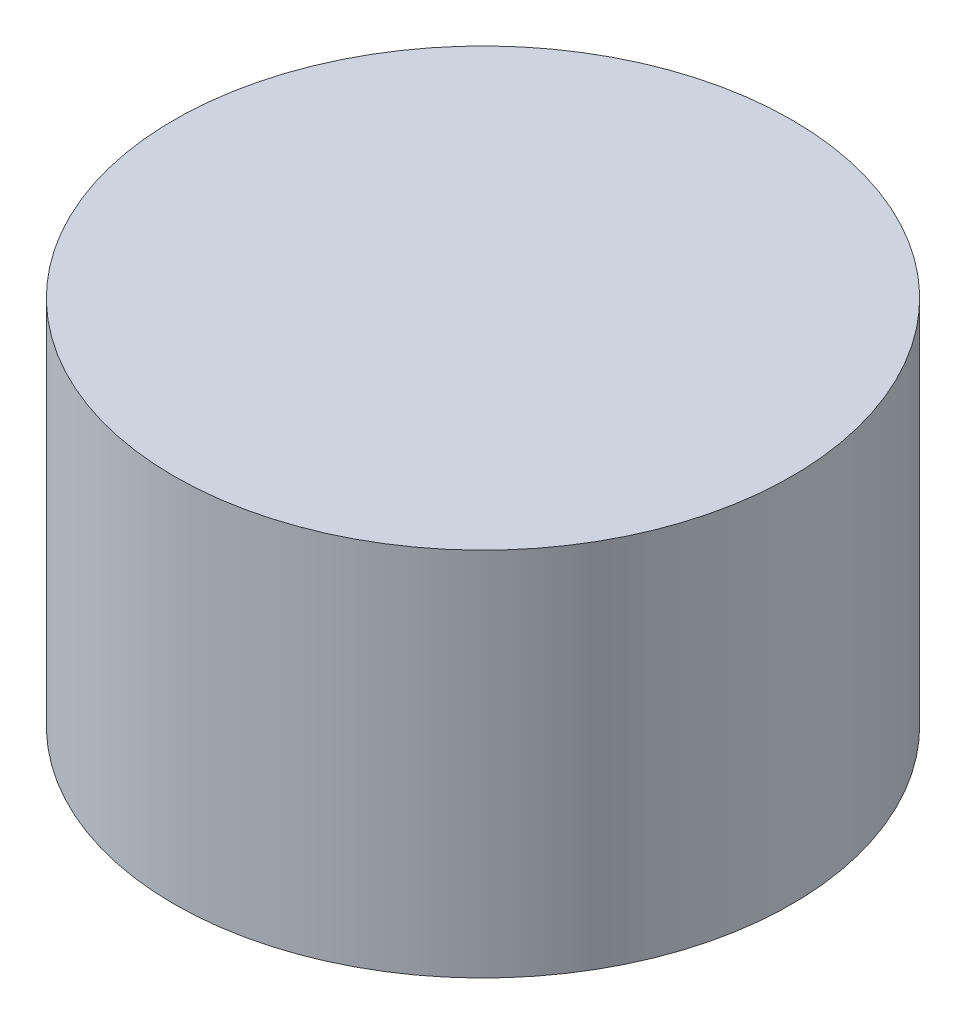
SolidWorks part; units mm, degrees
material "1023 Carbon Steel Sheet (SS)"
ref_plane "Front Plane" through (0, 0, 0) normal (0, 0, 1) x (1, 0, 0)
ref_plane "Top Plane" through (0, 0, 0) normal (0, 1, 0) x (1, 0, 0)
ref_plane "Right Plane" through (0, 0, 0) normal (1, 0, 0) x (0, 0, -1)
sketch "Sketch1" plane through (0, 0, 0) normal (0, 1, 0) x (1, 0, 0)
  circle A0 centre (0, 0) radius 25
  dimension "D1" = 50
extrude "Boss-Extrude1" add sketch "Sketch1" along normal blind 30
